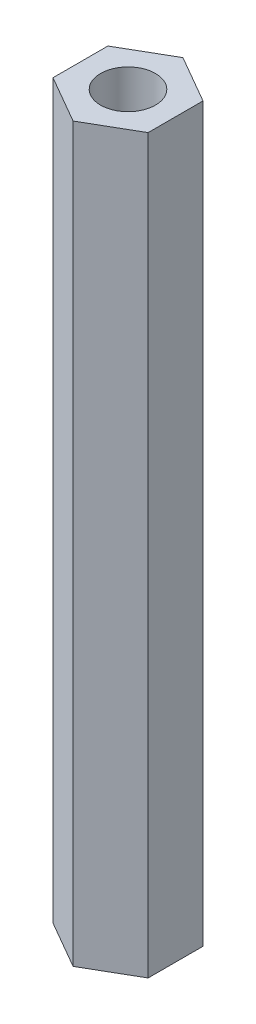
SolidWorks part; units mm, degrees
ref_plane "Front Plane" through (0, 0, 0) normal (0, 0, 1) x (1, 0, 0)
ref_plane "Top Plane" through (0, 0, 0) normal (0, 1, 0) x (1, 0, 0)
ref_plane "Right Plane" through (0, 0, 0) normal (1, 0, 0) x (0, 0, -1)
sketch "Sketch1" plane through (0, 0, 0) normal (0, 1, 0) x (1, 0, 0)
  line L0 (0, -3) -> (0, 3) construction
  line L1 (-2.5981, -1.5) -> (2.5981, 1.5) construction
  line L2 (2.5981, -1.5) -> (-2.5981, 1.5) construction
  line L3 (0, 3) -> (-2.5981, 1.5)
  line L4 (-2.5981, 1.5) -> (-2.5981, -1.5)
  line L5 (-2.5981, -1.5) -> (0, -3)
  line L6 (0, -3) -> (2.5981, -1.5)
  line L7 (2.5981, -1.5) -> (2.5981, 1.5)
  line L8 (2.5981, 1.5) -> (0, 3)
  circle A0 centre (0, 0) radius 1.5
  circle A1 centre (0, 0) radius 3 construction
  point P7 (0, 0)
  point P10 (0, 0)
  point P13 (0, 0)
extrude "Boss-Extrude1" add sketch "Sketch1" along normal blind 40
